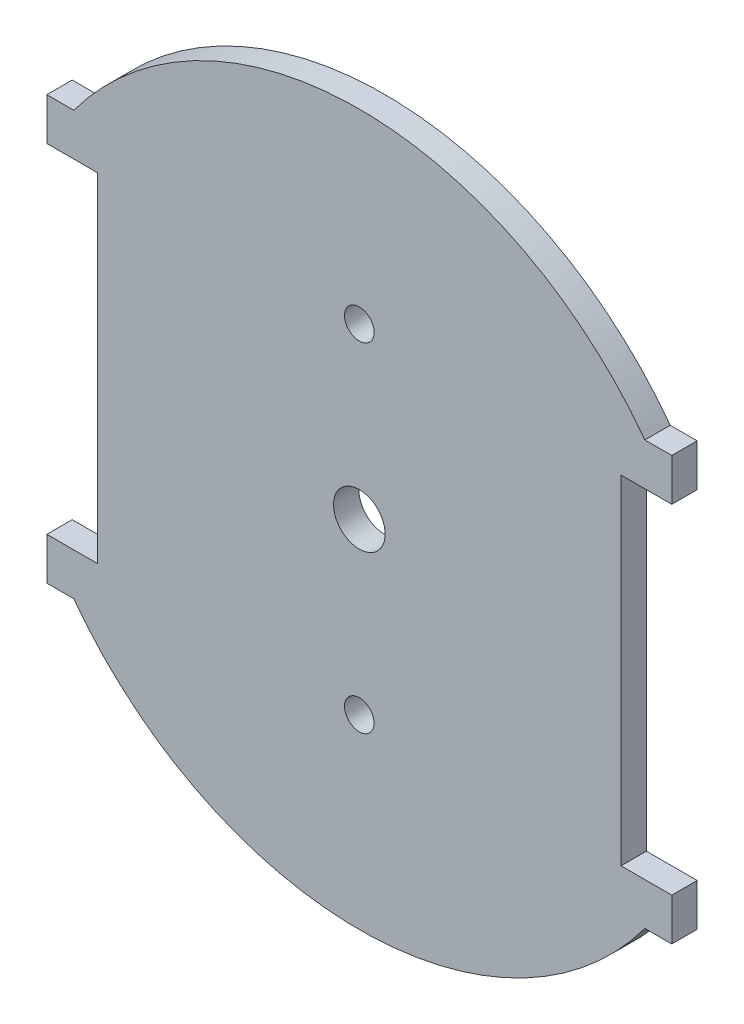
SolidWorks part; units mm, degrees
ref_plane "Alzado" through (0, 0, 0) normal (0, 0, 1) x (1, 0, 0)
ref_plane "Planta" through (0, 0, 0) normal (0, 1, 0) x (1, 0, 0)
ref_plane "Vista lateral" through (0, 0, 0) normal (1, 0, 0) x (0, 0, -1)
sketch "Croquis1" plane through (0, 0, 0) normal (0, 0, 1) x (1, 0, 0)
  line L0 (-30.9324, 20) -> (-18.7228, 20) construction
  line L1 (-36.9324, 20) -> (-30.9324, 20)
  line L2 (-30.9324, 20) -> (-30.9324, -20)
  line L3 (-18.7228, -20) -> (-30.9324, -20) construction
  line L4 (-30.9324, 20) -> (-30.9324, 11.75) construction
  line L5 (-36.9324, -20) -> (36.9324, 20) construction
  line L6 (-36.9324, 20) -> (36.9324, -20) construction
  line L7 (-36.9324, -20) -> (-30.9324, -20)
  line L8 (-36.9324, 20) -> (-36.9324, 25)
  line L9 (36.9324, 20) -> (30.9324, 20)
  line L10 (-36.9324, 25) -> (-33.7491, 25)
  line L11 (36.9324, -20) -> (30.9324, -20)
  line L12 (30.9324, 20) -> (30.9324, -20)
  line L13 (36.9324, 20) -> (36.9324, 25)
  line L14 (36.9324, 25) -> (33.7491, 25)
  line L15 (-36.9324, -20) -> (-36.9324, -25)
  line L16 (-36.9324, -25) -> (-33.7491, -25)
  line L17 (36.9324, -20) -> (36.9324, -25)
  line L18 (36.9324, -25) -> (33.7491, -25)
  arc A0 (-33.7491, -25) -> (33.7491, -25) centre (0, 0) ccw
  arc A1 (33.7491, 25) -> (-33.7491, 25) centre (0, 0) ccw
  circle A2 centre (0, 0) radius 3.05
  circle A3 centre (0, 20) radius 1.75
  circle A4 centre (0, -20) radius 1.75
  dimension "D1" = 40
  dimension "D2" = 20
  dimension "D5" = 40
  dimension "D6" = 42
  dimension "D3" = 6
  dimension "D4" = 6
  dimension "D7" = 5
  dimension "D8" = 5
extrude "Saliente-Extruir1" add sketch "Croquis1" along normal blind 3
